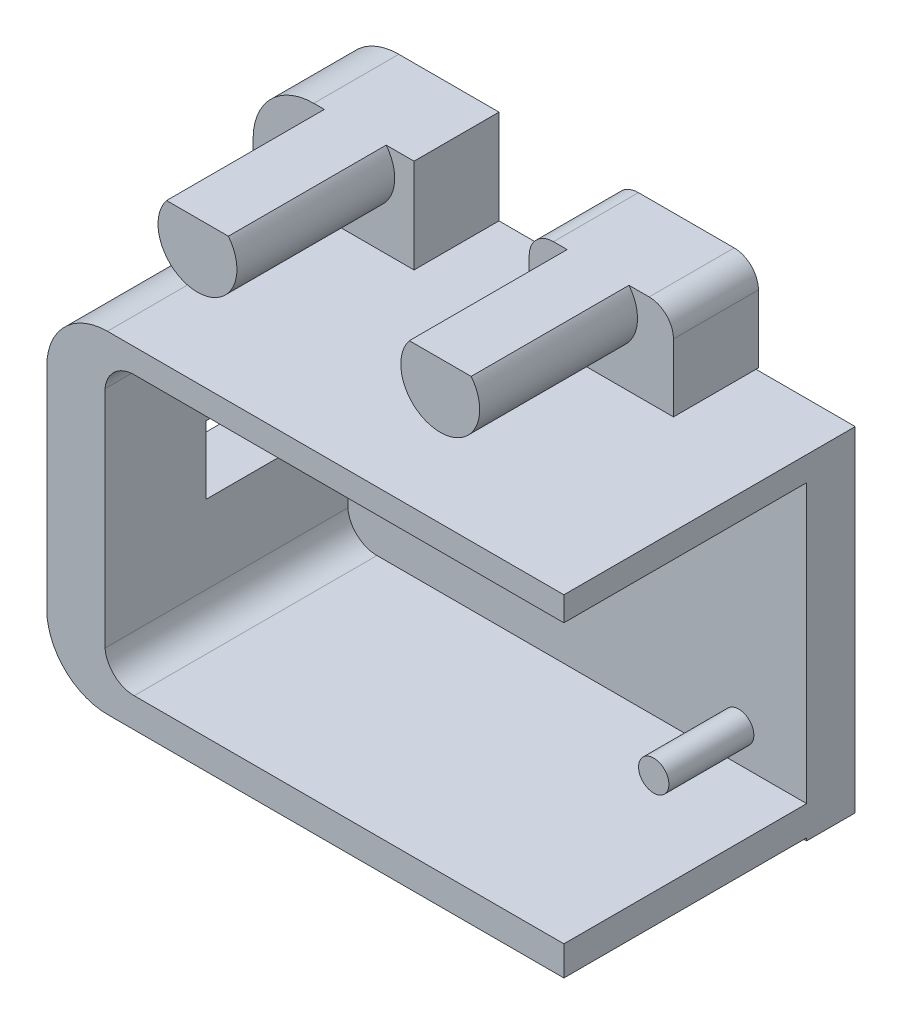
SolidWorks part; units mm, degrees
ref_plane "Front Plane" through (0, 0, 0) normal (0, 0, 1) x (1, 0, 0)
ref_plane "Top Plane" through (0, 0, 0) normal (0, 1, 0) x (1, 0, 0)
ref_plane "Right Plane" through (0, 0, 0) normal (1, 0, 0) x (0, 0, -1)
sketch "Sketch1" plane through (0, 0, 43.7867) normal (0, 0, -1) x (-1, 0, 0)
  line L0 (33.9918, 7.3397) -> (34.2823, 7.0196)
  line L1 (34.2823, 7.0196) -> (29.1897, 7.0196)
  line L2 (49.1897, 7.0196) -> (54.2823, 7.0196)
  circle A0 centre (31.736, 5) radius 3.25
  circle A1 centre (51.736, 5) radius 3.25
extrude "Boss-Extrude1" add sketch "Sketch1" against normal blind 11 and the other way blind 2 contours L1 A0 | L2 A1
sketch "Sketch2" plane through (0, 0, 41.7867) normal (0, 0, -1) x (-1, 0, 0)
  line L5 (17.5501, -25.6422) -> (17.5501, -2.7422)
  line L6 (17.5501, -2.7422) -> (52.9501, -2.7422)
  line L7 (55.3501, -4.9422) -> (55.3501, -23.4422)
  line L8 (52.9501, -25.6422) -> (17.5501, -25.6422)
  line L9 (17.5501, -2.7422) -> (17.5501, -0.7422)
  line L10 (17.5501, -0.7422) -> (60.1501, -0.7422)
  line L11 (60.1501, -0.7422) -> (60.1501, -28.0818)
  line L12 (60.1501, -28.0818) -> (17.5501, -28.0818)
  line L13 (17.5501, -25.6422) -> (17.5501, -28.0818)
  line L14 (55.1501, -4.9422) -> (55.1501, -23.4422) construction
  line L15 (18.1501, -2.9422) -> (53.1501, -2.9422) construction
  line L16 (53.1501, -25.4422) -> (18.1501, -25.4422) construction
  arc A3 (52.9501, -2.7422) -> (55.3501, -4.9422) centre (52.9585, -5.1422) cw
  arc A4 (55.3501, -23.4422) -> (52.9501, -25.6422) centre (52.9585, -23.2423) cw
  point P13 (35.6501, -25.4422)
  dimension "D1" = 0.2
  dimension "D2" = 0.2
  dimension "D3" = 0.2
extrude "Boss-Extrude2" add sketch "Sketch2" against normal blind 17 and the other way blind 3 separate body contours L7 A4 L8 L13 L12 L11 L10 L9 L6 A3
sketch "Sketch3" plane through (-60.1501, 0, 0) normal (-1, 0, 0) x (0, 0, 1)
  line L0 (50.1618, -11.6922) -> (50.1618, -16.6922) construction
  line L1 (50.1618, -11.6922) -> (42.8336, -11.6922) construction
  line L2 (50.1618, -16.6922) -> (42.8336, -16.6922) construction
  line L3 (42.8336, -11.6922) -> (42.8336, -16.6922) construction
  line L4 (50.4618, -11.3922) -> (50.4618, -16.9922)
  line L5 (50.4618, -16.9922) -> (42.5336, -16.9922)
  line L6 (42.5336, -11.3922) -> (42.5336, -16.9922)
  line L7 (50.4618, -11.3922) -> (42.5336, -11.3922)
  point P0 (50.1618, -11.6922)
  dimension "D1" = 0.3
extrude "Cut-Extrude1" cut sketch "Sketch3" against normal blind 5
sketch "Sketch4" plane through (0, 0, 38.7867) normal (0, 0, -1) x (-1, 0, 0)
  line L0 (17.5501, -0.7422) -> (60.1501, -0.7422)
  line L1 (17.5501, -0.7422) -> (17.5501, -28.3015)
  line L2 (60.1501, -0.7422) -> (60.1501, -28.3015)
  line L3 (17.5501, -28.3015) -> (60.1501, -28.3015)
  circle A0 centre (23.1501, -5.4422) radius 1.25
  circle A1 centre (23.1501, -22.9422) radius 1.25
extrude "Boss-Extrude3" add sketch "Sketch4" along normal blind 4 contours A0 | L0 L1 L3 L2 | A1
sketch "Sketch5" plane through (0, 0, 34.7867) normal (0, 0, -1) x (-1, 0, 0)
  circle A0 centre (23.1501, -5.4422) radius 1.25
  circle A2 centre (23.1501, -22.9422) radius 1.25
extrude "Boss-Extrude4" add sketch "Sketch5" against normal blind 11
sketch "Sketch6" plane through (0, 0, 41.7867) normal (0, 0, -1) x (-1, 0, 0)
  line L1 (37.409, 7.0196) -> (25.5247, 7.0196)
  line L2 (37.409, 7.0196) -> (37.409, -0.5422)
  line L3 (37.409, -0.5422) -> (25.5247, -0.5422)
  line L4 (25.5247, 7.0196) -> (25.5247, -0.5422)
  line L5 (46.8965, 7.0196) -> (60.1501, 7.0196)
  line L6 (46.8965, 7.0196) -> (46.8965, -0.7422)
  line L7 (46.8965, -0.7422) -> (60.1501, -0.7422)
  line L8 (60.1501, 7.0196) -> (60.1501, -0.7422)
extrude "Boss-Extrude5" add sketch "Sketch6" along normal up to surface (7 mm away) up to face at (-38.8501, -14.5219, 34.7867)
fillet "Fillet1" radius 5 2 edges at (-60.1501, -0.7422, 50.2867) (-60.1501, -28.0818, 48.7867)
fillet "Fillet2" radius 5 1 edges at (-60.1501, -28.3015, 36.7867)
fillet "Fillet3" radius 5 1 edges at (-60.1501, 7.0196, 38.2867)
fillet "Fillet4" radius 2 2 edges at (-25.5247, 7.0196, 38.2867) (-37.409, 7.0196, 38.2867)
